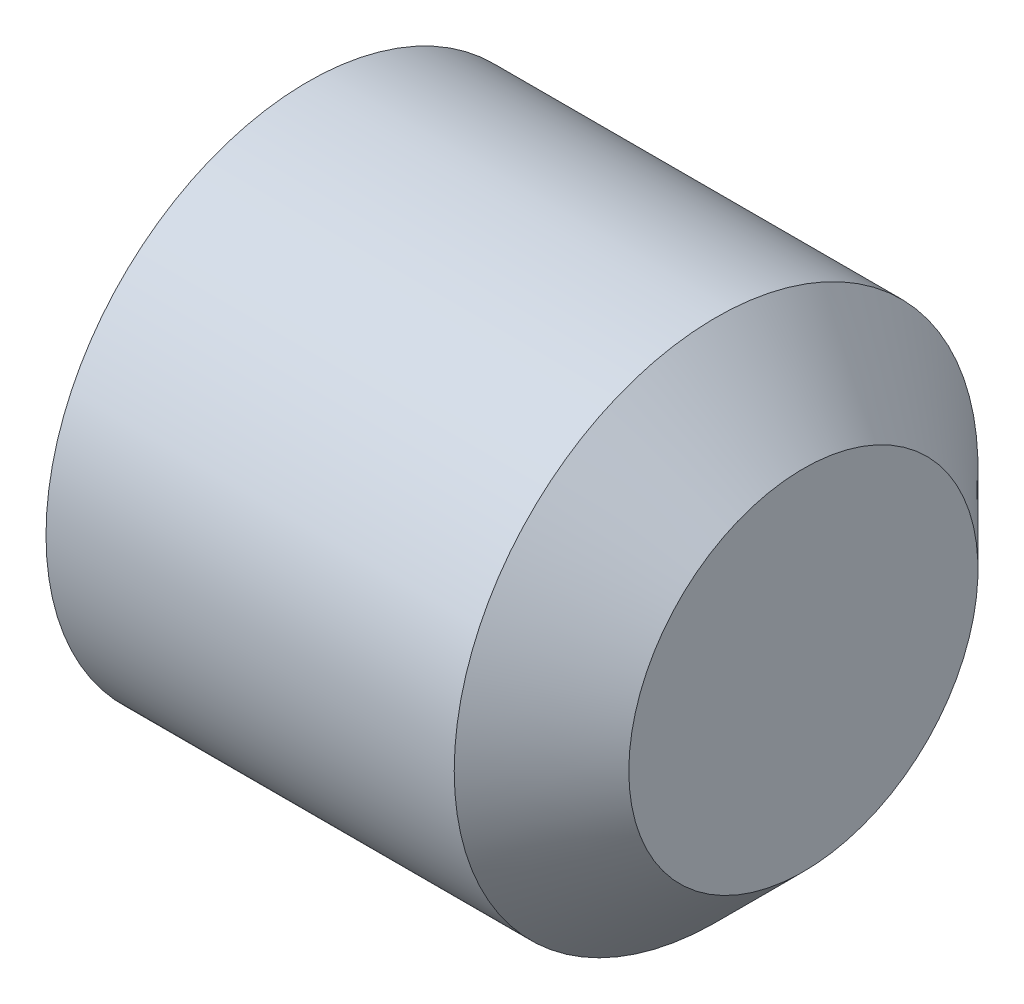
SolidWorks part; units mm, degrees
ref_plane "Plane1" through (0, 0, 0) normal (0, 0, 1) x (1, 0, 0)
ref_plane "Plane2" through (0, 0, 0) normal (0, 1, 0) x (1, 0, 0)
ref_plane "Plane3" through (0, 0, 0) normal (1, 0, 0) x (0, 0, -1)
sketch "BodySke" plane through (0, 0, 0) normal (0, 0, 1) x (1, 0, 0)
  line L0 (0, 0) -> (0, 1.2195)
  line L1 (0, 1.2195) -> (0.1619, 1.5)
  line L2 (0.1619, 1.5) -> (2.5, 1.5)
  line L3 (2.5, 1.5) -> (3, 1)
  line L4 (3, 0) -> (0, 0)
  line L5 (-12.7, 0) -> (88.9, 0) construction
  line L6 (3, 1) -> (3, 0)
  line L7 (3, 1) -> (3, 10.525) construction
  line L8 (0, -1.2195) -> (0.1619, -1.5) construction
  line L9 (0.5, 15.875) -> (0.5, -3.175) construction
  line L10 (2.5, -1.5) -> (3, -1) construction
  dimension "Length" = 3
  dimension "Diameter" = 3
  dimension "Drive_ch_ang" = 60
  dimension "Minor_dia" = 2.439
  dimension "Cup_nose_ang" = 45
  dimension "Cup_dia" = 2
  dimension "Advance" = 0.5
revolve "BaseBody" add sketch "BodySke" angle 360 about L5
cosmetic thread "ThreadCosmetic" [suppressed] parameters "Thread_minor"=2.439
sketch "Sketch2" plane through (0, 0, 0) normal (-1, 0, 0) x (0, 0, 1)
  line L0 (0.433, 0.75) -> (-0.433, 0.75)
  line L1 (-0.433, 0.75) -> (-0.866, 0)
  line L2 (0.433, 0.75) -> (0.866, 0)
  line L3 (0.433, -0.75) -> (0.866, 0)
  line L4 (0.433, -0.75) -> (-0.433, -0.75)
  line L5 (-0.433, -0.75) -> (-0.866, 0)
  dimension "Hex_size" = 1.5
  dimension "D2" = 0.75
  dimension "D3" = 0.75
extrude "Hex" cut sketch "Sketch2" against normal blind 1.2
sketch "ThdSchSke" plane through (0, 0, 0) normal (0, 0, 1) x (1, 0, 0)
  line L0 (0.1619, -1.2195) -> (-0.0345, -1.5)
  line L1 (0.1619, -1.2195) -> (0.3584, -1.5)
  line L2 (0.3584, -1.5) -> (0.3584, -1.875)
  line L3 (-3.175, 0) -> (5.1513, 0) construction
  line L5 (0.3584, -1.875) -> (-0.0345, -1.875)
  line L6 (-0.0345, -1.875) -> (-0.0345, -1.5)
  line L8 (0.1619, 1.5) -> (0.1619, -1.5) construction
  dimension "Thread_minor" = 2.439
  dimension "Diameter" = 3
  dimension "SideAngle" = 55
  dimension "VeeAngle" = 70
  dimension "Overcut" = 3.75
revolve "ThreadSchematic" [suppressed] cut sketch "ThdSchSke" angle 360 about L3
pattern_linear "ThdSchPat" [suppressed]
equation "\"D2@Sketch2\" = \"Hex_size@Sketch2\" / 2"
equation "\"D3@Sketch2\" = \"Hex_size@Sketch2\" / 2"
equation "\"Thread_minor@ThreadCosmetic\" = \"Minor_dia@BodySke\""
equation "\"Thread_minor@ThdSchSke\" = \"Thread_minor@ThreadCosmetic\""
equation "\"Diameter@ThdSchSke\" = \"Diameter@BodySke\""
equation "\"Overcut@ThdSchSke\" = \"Diameter@BodySke\" * 1.25"
equation "\"Num_threads@ThdSchPat\" = int( (\"Length@BodySke\" - ( ( ( \"Diameter@BodySke\" - \"Minor_dia@BodySke\" ) * 0.5 ) / tan( \"Drive_ch_ang@BodySke\" * 0.017453292 ) ) - ( ( ( \"Diameter@BodySke\" - \"Cup_dia@BodySke\" ) * 0.5 ) * tan( \"Cup_nose_ang@BodySke\" * 0.017453292 ) ) ) / \"Advance@BodySke\" + 0.999 )  + 1"
equation "\"Advance@ThdSchPat\" = (\"Length@BodySke\" - ( ( ( \"Diameter@BodySke\" - \"Minor_dia@BodySke\" ) * 0.5 ) / tan( \"Drive_ch_ang@BodySke\" * 0.017453292 ) ) - ( ( ( \"Diameter@BodySke\" - \"Cup_dia@BodySke\" ) * 0.5 ) * tan( \"Cup_nose_ang@BodySke\" * 0.017453292 ) ) ) /  (\"Num_threads@ThdSchPat\" - 1) 'relax it"
equation "' \"Num_threads@ThdSchPat\" = \"Num_threads@ThdSchPat\" - sgn( \"Num_threads@ThdSchPat\" - 1) '---chamfered tips only---"
